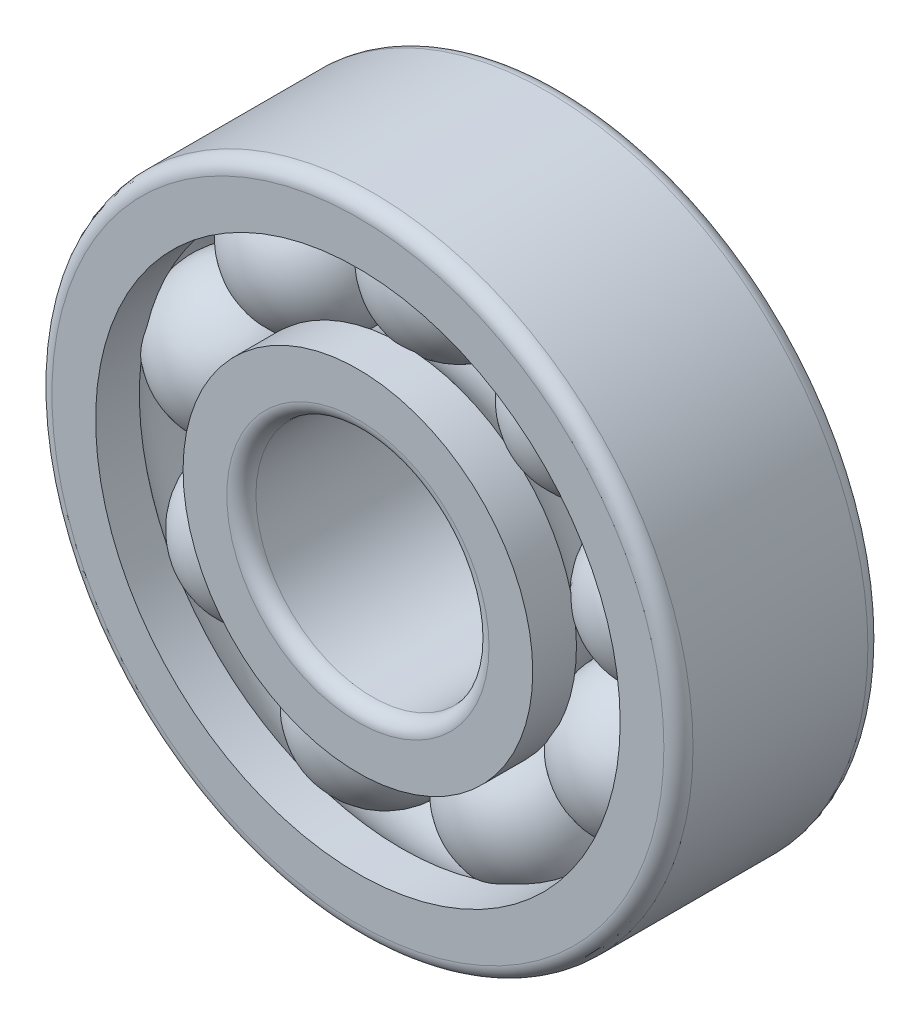
SolidWorks part; units mm, degrees
ref_plane "Front Plane" through (0, 0, 0) normal (0, 0, 1) x (1, 0, 0)
ref_plane "Top Plane" through (0, 0, 0) normal (0, 1, 0) x (1, 0, 0)
ref_plane "Right Plane" through (0, 0, 0) normal (1, 0, 0) x (0, 0, -1)
sketch "Sketch1" plane through (0, 0, 0) normal (0, 0, 1) x (1, 0, 0)
  circle A0 centre (0, 0) radius 11
  circle A1 centre (0, 0) radius 4
  circle A2 centre (0, 0) radius 6
  circle A3 centre (0, 0) radius 9
  dimension "D1" = 22
  dimension "D2" = 8
  dimension "D3" = 2
  dimension "D4" = 2
extrude "Boss-Extrude1" add sketch "Sketch1" along normal mid plane 7 contours A2 A1 | A0 A3
sketch "Sketch2" plane through (0, 0, 0) normal (1, 0, 0) x (0, 0, -1)
  line L0 (0, 0) -> (5.2512, 0) construction
  circle A0 centre (0, 7.5) radius 2.5
  dimension "D2" = 5
  dimension "D1" = 7.5
revolve "Cut-Revolve1" cut sketch "Sketch2" angle 360 about L0
sketch "Sketch4" plane through (0, 0, 0) normal (1, 0, 0) x (0, 0, -1)
  line L0 (0, 7.5) -> (9.4471, 7.5) construction
  line L1 (-2.55, 7.5) -> (2.55, 7.5)
  arc A0 (2.55, 7.5) -> (-2.55, 7.5) centre (0, 7.5) ccw
  dimension "D2" = 5.1
  dimension "D1" = 7.5
revolve "Revolve1" add sketch "Sketch4" angle 360 about L0
pattern_circular "CirPattern1" count 9 over 360 about axis through (0, 0, 0) along (0, 0, 1) of "Revolve1"
fillet "Fillet3" radius 0.5 4 edges at (4, 0, -3.5) (11, 0, -3.5) (4, 0, 3.5) (11, 0, 3.5)
